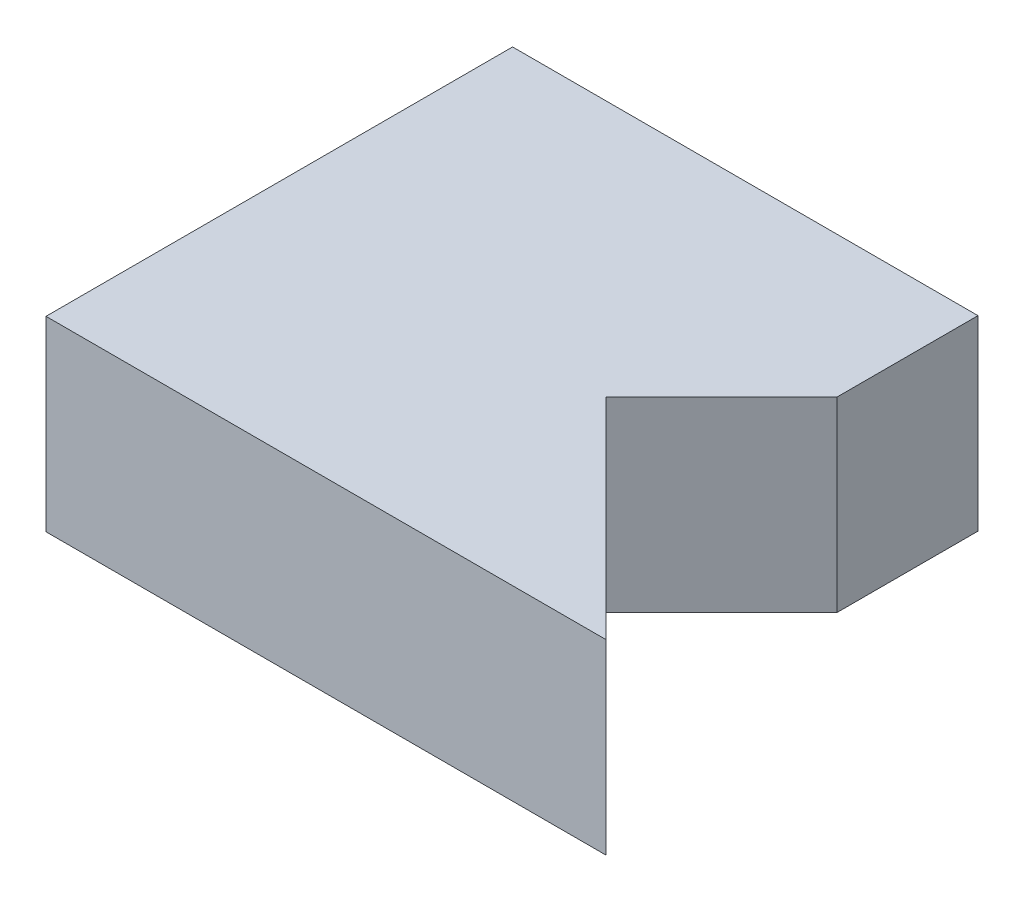
SolidWorks part; units mm, degrees
ref_plane "Plan de face" through (0, 0, 0) normal (0, 0, 1) x (1, 0, 0)
ref_plane "Plan de dessus" through (0, 0, 0) normal (0, 1, 0) x (1, 0, 0)
ref_plane "Plan de droite" through (0, 0, 0) normal (1, 0, 0) x (0, 0, -1)
sketch "Esquisse1" plane through (0, 0, 0) normal (0, 1, 0) x (1, 0, 0)
  line L0 (0, 0) -> (120, 0)
  line L1 (120, 0) -> (75, 45)
  line L2 (75, 45) -> (99.7487, 69.7487)
  line L3 (99.7487, 69.7487) -> (99.7487, 100)
  line L4 (99.7487, 100) -> (0, 100)
  line L5 (0, 100) -> (0, 0)
  dimension "D1" = 120
  dimension "D2" = 100
  dimension "D3" = 75
  dimension "D4" = 45
  dimension "D5" = 35
extrude "Boss.-Extru.1" add sketch "Esquisse1" along normal blind 40
